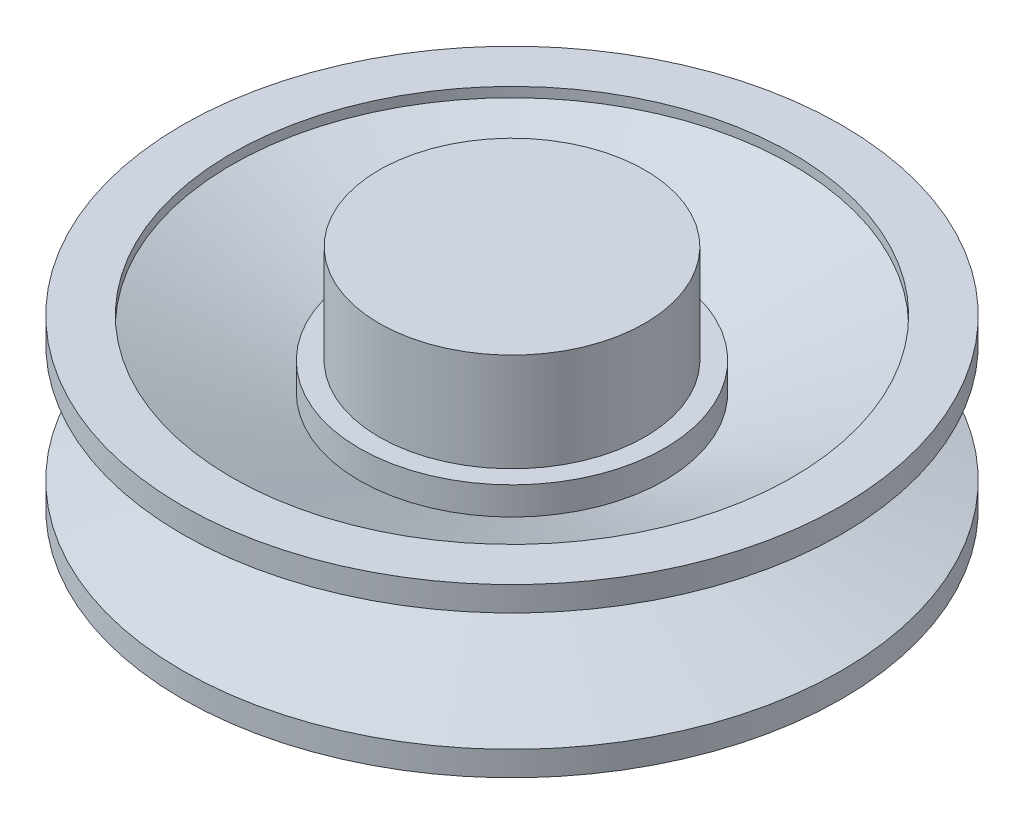
SolidWorks part; units mm, degrees
ref_plane "Front Plane" through (0, 0, 0) normal (0, 0, 1) x (1, 0, 0)
ref_plane "Top Plane" through (0, 0, 0) normal (0, 1, 0) x (1, 0, 0)
ref_plane "Right Plane" through (0, 0, 0) normal (1, 0, 0) x (0, 0, -1)
sketch "Sketch4" plane through (0, 0, 0) normal (1, 0, 0) x (0, 0, -1)
  line L0 (0, 25) -> (0, -25)
  line L1 (0, 25) -> (-27, 25)
  line L2 (-27, 25) -> (-27, 5)
  line L3 (-27, 5) -> (-31, 5)
  line L7 (-31, -0.6702) -> (-57, 10.9035)
  line L8 (-57, 10.9035) -> (-57, 12.9035)
  line L9 (-57, 12.9035) -> (-67, 12.9035)
  line L10 (-67, 12.9035) -> (-67, 7.9035)
  line L13 (-67, -16.0965) -> (-67, -21.0965)
  line L14 (-67, -21.0965) -> (-57, -21.0965)
  line L15 (-57, -21.0965) -> (-57, -19.0965)
  line L16 (-57, -19.0965) -> (-31, -11.639)
  line L17 (-31, -11.639) -> (-31, -25)
  line L18 (-31, -25) -> (0, -25)
  line L19 (-31, 5) -> (-31, -0.6702)
  line L22 (-67, 7.9035) -> (-42, -3.225)
  line L23 (-42, -3.225) -> (-42, -8.9259)
  line L24 (-42, -8.9259) -> (-67, -16.0965)
  point P4 (0, 0)
  point P24 (-66.8858, -16.0963)
  point P25 (-31.6298, 0)
  point P26 (-32.1859, -10.0905)
  point P27 (0, 0)
  point P28 (0, 0)
  dimension "D2" = 50
  dimension "D3" = 27
  dimension "D4" = 20
  dimension "D5" = 40
  dimension "D6" = 25
  dimension "D7" = 34
  dimension "D8" = 36
  dimension "D9" = 67
  dimension "D10" = 57
  dimension "D12" = 5
  dimension "D14" = 2
revolve "Revolve1" add sketch "Sketch4" angle 360 about L0
